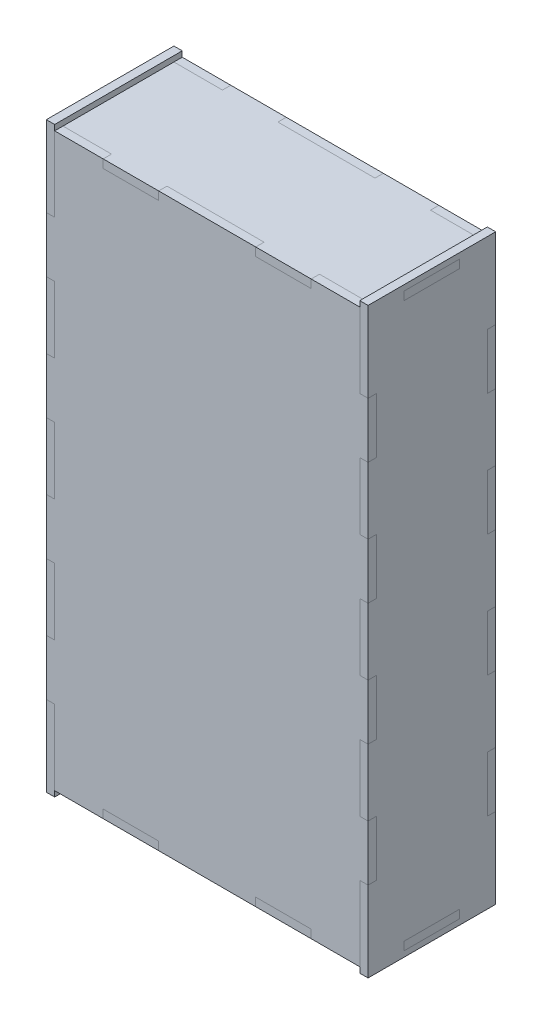
SolidWorks part; units mm, degrees
ref_plane "Front Plane" through (0, 0, 0) normal (0, 0, 1) x (1, 0, 0)
ref_plane "Top Plane" through (0, 0, 0) normal (0, 1, 0) x (1, 0, 0)
ref_plane "Right Plane" through (0, 0, 0) normal (1, 0, 0) x (0, 0, -1)
sketch "Sketch1" plane through (0, 0, 0) normal (0, 1, 0) x (1, 0, 0)
  line L0 (0, 40) -> (0, 30) construction
  line L1 (0, 0) -> (17.5, 0)
  line L2 (0, 0) -> (0, 10)
  line L3 (0, 40) -> (17.5, 40)
  line L4 (110, 0) -> (110, 10)
  line L5 (0, 30) -> (0, 40) construction
  line L6 (0, 10) -> (0, 0) construction
  line L7 (0, 40) -> (17.5, 40) construction
  line L8 (0, 10) -> (-3, 10)
  line L10 (0, 30) -> (-3, 30)
  line L11 (-3, 10) -> (-3, 30)
  line L12 (55, 40) -> (37.5, 40) construction
  line L13 (55, 40) -> (37.5, 40) construction
  line L16 (17.5, 40) -> (17.5, 43)
  line L17 (17.5, 43) -> (37.5, 43)
  line L18 (37.5, 40) -> (37.5, 43)
  line L20 (17.5, 0) -> (17.5, -3)
  line L21 (37.5, 0) -> (37.5, -3)
  line L22 (17.5, -3) -> (37.5, -3)
  line L23 (72.5, 40) -> (72.5, 43)
  line L24 (92.5, 40) -> (92.5, 43)
  line L25 (92.5, 43) -> (72.5, 43)
  line L26 (92.5, 0) -> (92.5, -3)
  line L27 (72.5, 0) -> (72.5, -3)
  line L28 (92.5, -3) -> (72.5, -3)
  line L29 (110, 10) -> (113, 10)
  line L30 (110, 30) -> (113, 30)
  line L31 (113, 10) -> (113, 30)
  line L32 (37.5, 40) -> (72.5, 40)
  line L33 (37.5, 40) -> (72.5, 40) construction
  line L34 (17.5, 40) -> (0, 40) construction
  line L35 (17.5, 40) -> (0, 40) construction
  line L36 (37.5, 0) -> (72.5, 0)
  line L37 (0, 10) -> (0, 0) construction
  line L38 (0, 30) -> (0, 40)
  line L39 (92.5, 40) -> (110, 40)
  line L40 (92.5, 40) -> (110, 40) construction
  line L41 (110, 30) -> (110, 40)
  line L42 (92.5, 0) -> (110, 0)
  point P10 (-1.5, 30)
  point P12 (27.5, 40)
  dimension "D1" = 110
  dimension "D2" = 40
  dimension "D3" = 20
  dimension "D4" = 1.5
  dimension "D5" = 3
  dimension "D7" = 20
extrude "Boss-Extrude1" add sketch "Sketch1" along normal blind 3
sketch "Sketch3" plane through (-3, 0, 0) normal (-1, 0, 0) x (0, 0, 1)
  line L2 (-20, -2) -> (-43, -2) construction
  line L3 (3, 3) -> (3, 27)
  line L4 (-43, -2) -> (3, -2)
  line L5 (-43, -2) -> (-43, 27)
  line L6 (-43, 208) -> (3, 208)
  line L7 (3, -2) -> (3, 27)
  line L8 (-30, 3) -> (-10, 3)
  line L9 (-30, 3) -> (-30, 0)
  line L10 (-30, 0) -> (-10, 0)
  line L11 (-10, 3) -> (-10, 0)
  line L13 (3, 27) -> (0, 27)
  line L15 (3, 47) -> (0, 47)
  line L16 (0, 27) -> (0, 47)
  line L17 (-43, 47) -> (-40, 47)
  line L18 (-40, 27) -> (-40, 47)
  line L19 (-43, 27) -> (-40, 27)
  line L21 (-43, 91) -> (-40, 91)
  line L22 (-40, 71) -> (-40, 91)
  line L23 (-43, 71) -> (-40, 71)
  line L26 (3, 71) -> (0, 71)
  line L27 (0, 71) -> (0, 91)
  line L28 (3, 91) -> (0, 91)
  line L29 (-43, 135) -> (-40, 135)
  line L30 (-40, 115) -> (-40, 135)
  line L31 (-43, 115) -> (-40, 115)
  line L34 (3, 115) -> (0, 115)
  line L35 (0, 115) -> (0, 135)
  line L36 (3, 135) -> (0, 135)
  line L37 (-43, 179) -> (-40, 179)
  line L38 (-40, 159) -> (-40, 179)
  line L39 (-43, 159) -> (-40, 159)
  line L42 (3, 159) -> (0, 159)
  line L43 (0, 159) -> (0, 179)
  line L44 (3, 179) -> (0, 179)
  line L46 (-30, 206) -> (-10, 206)
  line L47 (-10, 203) -> (-10, 206)
  line L48 (-30, 203) -> (-10, 203)
  line L49 (-30, 203) -> (-30, 206)
  line L50 (3, 47) -> (3, 71)
  line L51 (-43, 47) -> (-43, 71)
  line L52 (-43, 91) -> (-43, 115)
  line L53 (3, 91) -> (3, 115)
  line L54 (-43, 135) -> (-43, 159)
  line L55 (3, 135) -> (3, 159)
  line L56 (-43, 179) -> (-43, 208)
  line L57 (3, 179) -> (3, 208)
  line M49 (-30, 0) -> (-10, 0)
  line M50 (-10, 0) -> (-10, 3)
  line M51 (-10, 3) -> (-30, 3)
  line M52 (-30, 3) -> (-30, 0)
  dimension "D2" = 23
  dimension "D3" = 46
  dimension "D4" = 210
  dimension "D5" = 24
  dimension "D6" = 20
  dimension "D7" = 4
extrude "Boss-Extrude4" add sketch "Sketch3" against normal blind 3 separate body contours L44 L57 L6 L56 L37 L38 L39 L54 L29 L30 L31 L52 L21 L22 L23 L51 L17 L18 L19 L5 L4 L7 L3 L13 L16 L15 L50 L26 L27 L28 L53 L34 L35 L36 L55 L42 L43 L48 L49 L46 L47 M49 M52 M51 M50
pattern_linear "LPattern1" count 2 spacing 113 along (1, 0, 0) of bodies 104
pattern_linear "LPattern2" count 2 spacing 203 along (0, 1, 0) of bodies 101
sketch "Sketch6" plane through (0, 0, 3) normal (0, 0, 1) x (1, 0, 0)
  line L0 (0, -2) -> (0, 27) construction
  line L1 (17.5, 3) -> (37.5, 3)
  line L2 (0, 3) -> (0, 27)
  line L3 (17.5, 203) -> (37.5, 203)
  line L4 (110, 3) -> (110, 27)
  line L5 (0, 3) -> (0, 0) construction
  line L6 (92.5, 203) -> (110, 203) construction
  line L7 (110, 206) -> (110, 203) construction
  line L8 (92.5, 206) -> (92.5, 203) construction
  line L9 (110, 179) -> (110, 208) construction
  line L10 (110, 179) -> (113, 179)
  line L12 (110, 159) -> (113, 159)
  line L13 (113, 179) -> (113, 159)
  line L14 (113, 179) -> (110, 179) construction
  line L15 (113, 159) -> (110, 159) construction
  line L16 (113, 159) -> (113, 179) construction
  line L17 (113, 135) -> (110, 135) construction
  line L18 (110, 135) -> (113, 135)
  line L20 (110, 115) -> (113, 115)
  line L21 (113, 135) -> (113, 115)
  line L22 (110, 135) -> (110, 159) construction
  line L23 (113, 115) -> (110, 115) construction
  line L24 (113, 91) -> (113, 115) construction
  line L25 (113, 91) -> (110, 91) construction
  line L26 (110, 91) -> (113, 91)
  line L28 (110, 71) -> (113, 71)
  line L29 (113, 91) -> (113, 71)
  line L30 (110, 71) -> (110, 91) construction
  line L31 (113, 71) -> (110, 71) construction
  line L32 (113, 71) -> (113, 91) construction
  line L33 (113, 47) -> (110, 47) construction
  line L34 (110, 47) -> (113, 47)
  line L36 (110, 27) -> (113, 27)
  line L37 (113, 47) -> (113, 27)
  line L38 (113, -2) -> (113, 27) construction
  line L39 (113, 27) -> (113, 47) construction
  line L40 (92.5, 3) -> (92.5, 0) construction
  line L42 (92.5, 3) -> (92.5, 0)
  line L43 (92.5, 0) -> (110, 0)
  line L44 (110, 3) -> (110, 0)
  line L45 (92.5, 3) -> (110, 3) construction
  line L46 (110, -2) -> (110, 27) construction
  line L47 (92.5, 0) -> (110, 0) construction
  line L48 (72.5, 3) -> (72.5, 0) construction
  line L50 (72.5, 3) -> (72.5, 0)
  line L51 (72.5, 0) -> (37.5, 0)
  line L52 (37.5, 3) -> (37.5, 0)
  line L53 (72.5, 3) -> (72.5, 0) construction
  line L54 (37.5, 0) -> (72.5, 0) construction
  line L55 (17.5, 3) -> (17.5, 0) construction
  line L57 (17.5, 3) -> (17.5, 0)
  line L58 (17.5, 0) -> (0, 0)
  line L59 (0, 3) -> (0, 0)
  line L60 (17.5, 3) -> (17.5, 0) construction
  line L61 (0, 27) -> (-3, 27) construction
  line L62 (0, 27) -> (-3, 27)
  line L64 (0, 47) -> (-3, 47)
  line L65 (-3, 27) -> (-3, 47)
  line L66 (-3, 47) -> (-3, 71) construction
  line L67 (0, 47) -> (-3, 47) construction
  line L68 (0, 71) -> (-3, 71) construction
  line L69 (0, 71) -> (-3, 71)
  line L71 (0, 91) -> (-3, 91)
  line L72 (-3, 71) -> (-3, 91)
  line L73 (0, 71) -> (-3, 71) construction
  line L74 (-3, 71) -> (-3, 91) construction
  line L75 (0, 91) -> (0, 115) construction
  line L76 (0, 115) -> (-3, 115)
  line L78 (0, 135) -> (-3, 135)
  line L79 (-3, 115) -> (-3, 135)
  line L80 (0, 115) -> (0, 135) construction
  line L81 (-3, 115) -> (-3, 135) construction
  line L82 (0, 159) -> (-3, 159) construction
  line L83 (0, 159) -> (-3, 159)
  line L85 (0, 179) -> (-3, 179)
  line L86 (-3, 159) -> (-3, 179)
  line L87 (0, 135) -> (0, 159) construction
  line L88 (-3, 179) -> (-3, 208) construction
  line L89 (0, 179) -> (-3, 179) construction
  line L90 (17.5, 206) -> (37.5, 206) construction
  line L92 (0, 203) -> (0, 206)
  line L93 (0, 206) -> (17.5, 206)
  line L94 (17.5, 203) -> (17.5, 206)
  line L95 (17.5, 206) -> (17.5, 203) construction
  line L96 (37.5, 206) -> (37.5, 203) construction
  line L98 (37.5, 203) -> (37.5, 206)
  line L99 (37.5, 206) -> (72.5, 206)
  line L100 (72.5, 203) -> (72.5, 206)
  line L101 (37.5, 203) -> (72.5, 203) construction
  line L102 (72.5, 206) -> (72.5, 203) construction
  line L103 (72.5, 206) -> (92.5, 206) construction
  line L105 (92.5, 203) -> (92.5, 206)
  line L106 (92.5, 206) -> (110, 206)
  line L107 (110, 203) -> (110, 206)
  line L108 (0, 179) -> (0, 203)
  line L109 (0, 135) -> (0, 159)
  line L110 (72.5, 3) -> (92.5, 3)
  line L111 (0, 47) -> (0, 71)
  line L112 (0, 91) -> (0, 115)
  line L113 (72.5, 203) -> (92.5, 203)
  line L114 (110, 179) -> (110, 203)
  line L115 (110, 135) -> (110, 159)
  line L116 (110, 47) -> (110, 71)
  line L117 (110, 91) -> (110, 115)
extrude "Boss-Extrude6" add sketch "Sketch6" against normal blind 3 separate body
pattern_linear "LPattern3" count 2 spacing 43 along (0, 0, -1) of bodies 108
